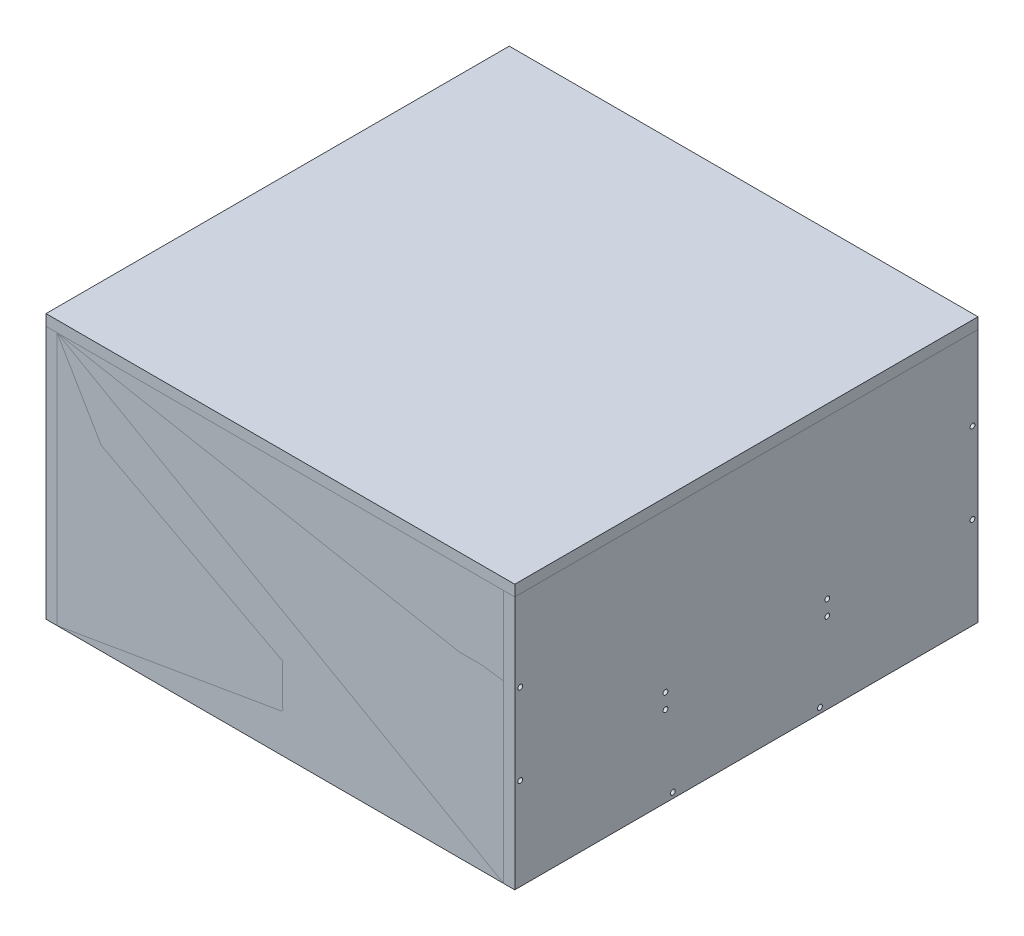
SolidWorks part; units mm, degrees
ref_plane "Front Plane" through (0, 0, 0) normal (0, 0, 1) x (1, 0, 0)
ref_plane "Top Plane" through (0, 0, 0) normal (0, 1, 0) x (1, 0, 0)
ref_plane "Right Plane" through (0, 0, 0) normal (1, 0, 0) x (0, 0, -1)
sketch "Sketch1" plane through (0, 0, 0) normal (0, 1, 0) x (1, 0, 0)
  line L1 (0, 0) -> (257.175, 0)
  line L2 (0, 0) -> (0, 254)
  line L3 (0, 254) -> (257.175, 254)
  line L4 (257.175, 0) -> (257.175, 254)
  dimension "D1" = 257.175
  dimension "D2" = 254
extrude "Boss-Extrude1" add sketch "Sketch1" against normal blind 6.35
sketch "Sketch2" plane through (0, 0, 0) normal (0, 0, 1) x (1, 0, 0)
  line L0 (257.175, -6.35) -> (257.175, 0) construction
  line L1 (0, -6.35) -> (257.175, -6.35)
  line L2 (0, -6.35) -> (0, 139.7)
  line L3 (0, 139.7) -> (257.175, 139.7)
  line L4 (257.175, -6.35) -> (257.175, 139.7)
  dimension "D1" = 146.05
extrude "Boss-Extrude2" add sketch "Sketch2" along normal blind 6.35 separate body
sketch "Sketch3" plane through (0, 0, 0) normal (0, -1, 0) x (1, 0, 0)
  line L0 (0, -127) -> (-23.5534, -127)
  line L1 (0, -254) -> (0, 0) construction
  line L2 (0, -127) -> (0, -138.9854)
ref_plane "Plane2" through (0, 0, -127) normal (0, 0, -1) x (-1, 0, 0)
mirror "Mirror1" about plane through (0, 0, -127) normal (0, 0, -1) of bodies 102
sketch "Sketch4" plane through (0, 0, 0) normal (-1, 0, 0) x (0, 0, 1)
  line L1 (-260.35, -6.35) -> (6.35, -6.35)
  line L2 (-260.35, -6.35) -> (-260.35, 139.7)
  line L3 (-260.35, 139.7) -> (6.35, 139.7)
  line L4 (6.35, -6.35) -> (6.35, 139.7)
extrude "Boss-Extrude3" add sketch "Sketch4" along normal blind 6.35 separate body
sketch "Sketch5" plane through (0, -6.35, 0) normal (0, -1, 0) x (1, 0, 0)
  line L0 (128.5875, 0) -> (-138.2478, 0)
  line L1 (0, 0) -> (257.175, 0) construction
ref_plane "Plane3" through (128.5875, -6.35, 0) normal (-1, 0, 0) x (0, 0, 1)
mirror "Mirror2" about plane through (128.5875, -6.35, 0) normal (-1, 0, 0) of bodies 104
sketch "Sketch6" plane through (0, 0, 0) normal (0, -1, 0) x (1, 0, 0)
  line L0 (128.5875, 0) -> (128.5875, -254)
  line L1 (0, 0) -> (257.175, 0) construction
  line L2 (257.175, -254) -> (0, -254) construction
  line L4 (122.2375, 0) -> (134.9375, 0)
  line L5 (122.2375, 0) -> (122.2375, -254)
  line L6 (122.2375, -254) -> (134.9375, -254)
  line L7 (134.9375, 0) -> (134.9375, -254)
  line L8 (122.2375, 0) -> (134.9375, -254) construction
  line L9 (122.2375, -254) -> (134.9375, 0) construction
  point P6 (128.5875, -127)
  dimension "D1" = 12.7
extrude "Boss-Extrude4" add sketch "Sketch6" against normal blind 57.15 separate body contours L5 L6 L7 L4
sketch "Sketch8" plane through (0, 57.15, 0) normal (0, 1, 0) x (-1, 0, 0)
  line L0 (-128.5875, -254) -> (-128.5875, -173.5667) construction
  line L2 (-122.2375, -254) -> (-134.9375, -254) construction
  line L3 (-128.5875, 0) -> (-128.5875, -80.4333) construction
  line L4 (-122.2375, 0) -> (-134.9375, 0) construction
  line L5 (-122.2375, 0) -> (-122.2375, -254) construction
  line L6 (-134.9375, -86.7833) -> (-122.2375, -86.7833)
  line L7 (-134.9375, -86.7833) -> (-134.9375, -74.0833)
  line L8 (-134.9375, -74.0833) -> (-122.2375, -74.0833)
  line L9 (-122.2375, -86.7833) -> (-122.2375, -74.0833)
  line L10 (-134.9375, -86.7833) -> (-122.2375, -74.0833) construction
  line L11 (-134.9375, -74.0833) -> (-122.2375, -86.7833) construction
  line L13 (-134.9375, -179.9167) -> (-122.2375, -179.9167)
  line L14 (-134.9375, -179.9167) -> (-134.9375, -167.2167)
  line L15 (-134.9375, -167.2167) -> (-122.2375, -167.2167)
  line L16 (-122.2375, -179.9167) -> (-122.2375, -167.2167)
  line L17 (-134.9375, -179.9167) -> (-122.2375, -167.2167) construction
  line L18 (-134.9375, -167.2167) -> (-122.2375, -179.9167) construction
  dimension "D1" = 80.4333
  dimension "D2" = 12.7
extrude "Cut-Extrude1" cut sketch "Sketch8" against normal blind 25.4
sketch "Sketch11" plane through (0, 31.75, 0) normal (0, 1, 0) x (-1, 0, 0)
  line L0 (-134.9375, -173.5667) -> (-128.5875, -173.5667) construction
  line L1 (0, -179.9167) -> (-257.175, -179.9167)
  line L2 (0, -179.9167) -> (0, -167.2167)
  line L3 (0, -167.2167) -> (-257.175, -167.2167)
  line L4 (-257.175, -179.9167) -> (-257.175, -167.2167)
  line L5 (0, -179.9167) -> (-257.175, -167.2167) construction
  line L6 (0, -167.2167) -> (-257.175, -179.9167) construction
  line L7 (-134.9375, -167.2167) -> (-134.9375, -179.9167) construction
  line L9 (0, -254) -> (0, 0) construction
  line L10 (-128.5875, -167.2167) -> (-128.5875, -173.5667) construction
  point P0 (-128.5875, -173.5667)
  dimension "D1" = 12.7
  dimension "D2" = 6.35
extrude "Boss-Extrude6" add sketch "Sketch11" along normal blind 25.4 separate body
mirror "Mirror3" about plane through (0, 0, -127) normal (0, 0, -1) of bodies 113
ref_plane "Plane4" through (257.175, 0, 0) normal (1, 0, 0) x (0, 0, -1)
sketch "Sketch21" plane through (-6.35, 0, 0) normal (-1, 0, 0) x (0, 0, 1)
  line L0 (-80.4333, 31.75) -> (-80.4333, 40.132) construction
  line L2 (-86.7833, 31.75) -> (-74.0833, 31.75) construction
  line L3 (-80.4333, 57.15) -> (-80.4333, 48.768) construction
  line L4 (-74.0833, 57.15) -> (-86.7833, 57.15) construction
  line L5 (-127, 57.15) -> (-127, 14.4604) construction
  line L6 (-86.7833, 57.15) -> (-167.2167, 57.15) construction
  line L7 (-173.5667, 31.75) -> (-173.5667, 40.132) construction
  line L8 (-173.5667, 57.15) -> (-173.5667, 48.768) construction
  line L9 (-257.175, 139.7) -> (-257.175, 93.1333) construction
  line L10 (-260.35, 139.7) -> (-254, 139.7) construction
  line L11 (-257.175, 0) -> (-257.175, 46.5667) construction
  line L12 (-254, -3.175) -> (-257.175, -3.175) construction
  line L13 (-254, -6.35) -> (-254, 0) construction
  line L14 (0, -3.175) -> (3.175, -3.175) construction
  line L15 (3.175, 0) -> (3.175, 46.5667) construction
  line L16 (3.175, 139.7) -> (3.175, 93.1333) construction
  line L17 (-254, -3.175) -> (-169.3418, -3.175) construction
  line L18 (0, -3.175) -> (-84.6582, -3.175) construction
  dimension "D1" = 8.382
  dimension "D2" = 46.5667
  dimension "D3" = 84.6582
hole_wizard "#4-40 Tapped Hole5" positions "3DSketch5" profile "Sketch23" tap size "#4-40" standard "Ansi Inch" end condition through all
sketch3d "3DSketch5"
  line L1 (-6.35, 139.7, 6.35) -> (-6.35, 139.7, -260.35) construction
  line L6 (-6.35, -6.35, -260.35) -> (-6.35, -6.35, 6.35) construction
  point P0 (-6.35, 93.1333, -257.175)
  point P3 (-6.35, 46.5667, -257.175)
  point P9 (-6.35, -3.175, -169.3418)
  point P12 (-6.35, -3.175, -84.6582)
  point P15 (-6.35, 40.132, -173.5667)
  point P18 (-6.35, 48.768, -173.5667)
  point P21 (-6.35, 48.768, -80.4333)
  point P24 (-6.35, 40.132, -80.4333)
  point P27 (-6.35, 46.5667, 3.175)
  point P30 (-6.35, 93.1333, 3.175)
  dimension "D1" = 46.5667
  dimension "D2" = 52.9167
sketch "Sketch23" plane through (-6.35, 93.1333, -257.175) normal (0, 1, 0) x (0, 0, 1)
  line L0 (0, 0) -> (0, 269.875)
  line L1 (0, 269.875) -> (1.397, 269.875)
  line L2 (1.397, 269.875) -> (1.397, 0)
  line L3 (263.525, 269.875) -> (-3.175, 269.875) construction
  line L5 (1.397, 0) -> (0, 0)
  line L11 (0, -6.35) -> (0, 107.95) construction
  dimension "Thread Major Dia." = 2.794
  dimension "Thru Tap Drill Depth" = 269.875
sketch "Sketch24" plane through (0, 0, 0) normal (0, 0, 1) x (1, 0, 0)
  line L0 (128.5875, 57.15) -> (128.5875, 40.2167) construction
  line L1 (122.2375, 57.15) -> (134.9375, 57.15) construction
  line L2 (128.5875, 140.4094) -> (128.5875, -153.1094) construction
  line L3 (128.5875, 0) -> (128.5875, 16.9333) construction
  line L4 (0, 0) -> (257.175, 0) construction
  dimension "D1" = 16.9333
hole_wizard "#4-40 Tapped Hole4" positions "3DSketch6" profile "Sketch25" tap size "#4-40" standard "Ansi Inch" end condition through all
sketch3d "3DSketch6"
  point P0 (128.5875, 40.2167, 0)
  point P3 (128.5875, 16.9333, 0)
sketch "Sketch25" plane through (128.5875, 40.2167, 0) normal (1, 0, 0) x (0, -1, 0)
  line L0 (0, 0) -> (0, 260.35)
  line L1 (0, 260.35) -> (1.397, 260.35)
  line L2 (1.397, 260.35) -> (1.397, 0)
  line L5 (1.397, 0) -> (0, 0)
  line L11 (0, -6.35) -> (0, 107.95) construction
  dimension "Thread Major Dia." = 2.794
  dimension "Thru Tap Drill Depth" = 260.35
sketch "Sketch26" plane through (0, 139.7, 0) normal (0, 1, 0) x (-1, 0, 0)
  line L1 (6.35, 6.35) -> (-263.525, 6.35)
  line L2 (6.35, 6.35) -> (6.35, -260.35)
  line L3 (6.35, -260.35) -> (-263.525, -260.35)
  line L4 (-263.525, 6.35) -> (-263.525, -260.35)
extrude "Boss-Extrude7" add sketch "Sketch26" along normal blind 6.35 separate body
sketch "Sketch34" plane through (263.525, 0, 0) normal (1, 0, 0) x (0, 0, -1)
  line L0 (257.175, 93.1333) -> (260.35, 93.1333)
  line L1 (260.35, 139.7) -> (260.35, -6.35) construction
  line L2 (257.175, 46.5667) -> (260.35, 46.5667)
  line L5 (169.3418, -3.175) -> (169.3418, -6.35)
  line L6 (260.35, -6.35) -> (-6.35, -6.35) construction
  line L7 (127, 139.7) -> (127, -6.35) construction
  line L8 (-6.35, 139.7) -> (260.35, 139.7) construction
  line L9 (84.6582, -3.175) -> (84.6582, -6.35)
  line L11 (-3.175, 46.5667) -> (-6.35, 46.5667)
  line L12 (-3.175, 93.1333) -> (-6.35, 93.1333)
sketch "Sketch35" plane through (0, 0, -260.35) normal (0, 0, -1) x (-1, 0, 0)
  line L0 (-263.525, 93.1333) -> (-224.4298, 93.1333) construction
  line L1 (-263.525, 46.5667) -> (-224.4298, 46.5667) construction
  line L2 (-257.175, 94.5303) -> (-257.175, 91.7363)
  line L3 (-231.775, 89.9583) -> (-231.775, 96.3083)
  line L4 (-257.175, -6.35) -> (-257.175, 139.7) construction
  line L5 (-257.175, -6.35) -> (-257.175, 139.7) construction
  line L6 (-257.175, 47.9637) -> (-257.175, 45.1697)
  line L7 (-231.775, 43.3917) -> (-231.775, 49.7417)
  line L8 (-244.475, 89.9583) -> (-244.475, 91.7363)
  line L9 (-244.475, 96.3083) -> (-231.775, 96.3083)
  line L10 (-244.475, 89.9583) -> (-231.775, 89.9583)
  line L11 (-257.175, 94.5303) -> (-244.475, 94.5303)
  line L12 (-263.525, 139.7) -> (-263.525, -6.35) construction
  line L13 (-257.175, 91.7363) -> (-244.475, 91.7363)
  line L14 (-244.475, 43.3917) -> (-244.475, 45.1697)
  line L15 (-244.475, 94.5303) -> (-244.475, 96.3083)
  line L16 (-263.525, 66.675) -> (-143.2647, 66.675) construction
  line L17 (-244.475, 49.7417) -> (-231.775, 49.7417)
  line L18 (-244.475, 43.3917) -> (-231.775, 43.3917)
  line L19 (-257.175, 47.9637) -> (-244.475, 47.9637)
  line L20 (-257.175, 45.1697) -> (-244.475, 45.1697)
  line L21 (-244.475, 47.9637) -> (-244.475, 49.7417)
  line L22 (6.35, 46.5667) -> (-32.7452, 46.5667) construction
  line L23 (6.35, 93.1333) -> (-32.7452, 93.1333) construction
  line L24 (-128.5875, 139.7) -> (-128.5875, 111.9581) construction
  line L25 (-257.175, 139.7) -> (0, 139.7) construction
  line L26 (-12.7, 47.9637) -> (-12.7, 49.7417)
  line L27 (0, 45.1697) -> (-12.7, 45.1697)
  line L28 (0, 47.9637) -> (-12.7, 47.9637)
  line L29 (-12.7, 43.3917) -> (-25.4, 43.3917)
  line L30 (-12.7, 49.7417) -> (-25.4, 49.7417)
  line L31 (-12.7, 94.5303) -> (-12.7, 96.3083)
  line L32 (-12.7, 43.3917) -> (-12.7, 45.1697)
  line L33 (0, 91.7363) -> (-12.7, 91.7363)
  line L34 (0, 94.5303) -> (-12.7, 94.5303)
  line L35 (-12.7, 89.9583) -> (-25.4, 89.9583)
  line L36 (-12.7, 96.3083) -> (-25.4, 96.3083)
  line L37 (-12.7, 89.9583) -> (-12.7, 91.7363)
  line L38 (-25.4, 43.3917) -> (-25.4, 49.7417)
  line L39 (0, 47.9637) -> (0, 45.1697)
  line L40 (-25.4, 89.9583) -> (-25.4, 96.3083)
  line L41 (0, 94.5303) -> (0, 91.7363)
  line L42 (-257.175, 139.7) -> (-257.175, -6.35) construction
  point P0 (-257.175, 93.1333)
  point P4 (-257.175, 46.5667)
  point P11 (-231.775, 93.1333)
  point P22 (-231.775, 46.5667)
  dimension "D1" = 2.794
  dimension "D2" = 12.7
  dimension "D3" = 6.35
  dimension "D4" = 12.7
  dimension "D5" = 6.35
  dimension "D6" = 12.7
  dimension "D7" = 2.794
  dimension "D8" = 12.7
extrude "Cut-Extrude2" cut sketch "Sketch35" against normal blind 6.35
sketch "Sketch38" plane through (-6.35, 0, 0) normal (-1, 0, 0) x (0, 0, 1)
  line L0 (-127, -6.35) -> (-140.9104, -6.35)
  line L1 (-260.35, -6.35) -> (6.35, -6.35) construction
ref_plane "Plane5" through (-6.35, -6.35, -127) normal (0, 0, -1) x (-1, 0, 0)
mirror "Mirror7" about plane through (-6.35, -6.35, -127) normal (0, 0, -1) of bodies 147
sketch "Sketch39" plane through (0, -6.35, 0) normal (0, -1, 0) x (1, 0, 0)
  line L0 (263.525, -169.3418) -> (-6.35, -169.3418) construction
  line L1 (-6.35, -260.35) -> (-6.35, 6.35) construction
  line L2 (263.525, -84.6582) -> (-6.35, -84.6582) construction
  line L3 (-6.35, -84.6582) -> (25.4, -84.6582) construction
  line L4 (0, -83.2612) -> (0, -86.0552)
  line L5 (25.4, -87.8332) -> (25.4, -81.4832)
  line L6 (12.7, -87.8332) -> (12.7, -86.0552)
  line L7 (12.7, -81.4832) -> (25.4, -81.4832)
  line L8 (12.7, -87.8332) -> (25.4, -87.8332)
  line L9 (0, -83.2612) -> (12.7, -83.2612)
  line L10 (0, -86.0552) -> (12.7, -86.0552)
  line L11 (12.7, -83.2612) -> (12.7, -81.4832)
  line L13 (0, -260.35) -> (0, 6.35) construction
  line L14 (-6.35, -169.3418) -> (19.2534, -169.3418) construction
  line L15 (0, -167.9448) -> (0, -170.7388)
  line L16 (25.4, -172.5168) -> (25.4, -166.1668)
  line L17 (12.7, -172.5168) -> (12.7, -170.7388)
  line L18 (12.7, -166.1668) -> (25.4, -166.1668)
  line L19 (12.7, -172.5168) -> (25.4, -172.5168)
  line L20 (0, -167.9448) -> (12.7, -167.9448)
  line L21 (0, -170.7388) -> (12.7, -170.7388)
  line L22 (12.7, -167.9448) -> (12.7, -166.1668)
  line L23 (0, -254) -> (0, 0) construction
  line L24 (128.5875, 6.35) -> (128.5875, -33.1685) construction
  line L25 (0, 6.35) -> (257.175, 6.35) construction
  line L26 (263.525, -169.3418) -> (237.9216, -169.3418) construction
  line L27 (263.525, -84.6582) -> (231.775, -84.6582) construction
  line L28 (244.475, -167.9448) -> (244.475, -166.1668)
  line L29 (257.175, -170.7388) -> (244.475, -170.7388)
  line L30 (257.175, -167.9448) -> (244.475, -167.9448)
  line L31 (244.475, -172.5168) -> (231.775, -172.5168)
  line L32 (244.475, -166.1668) -> (231.775, -166.1668)
  line L33 (244.475, -172.5168) -> (244.475, -170.7388)
  line L34 (231.775, -172.5168) -> (231.775, -166.1668)
  line L35 (257.175, -167.9448) -> (257.175, -170.7388)
  line L36 (244.475, -83.2612) -> (244.475, -81.4832)
  line L37 (257.175, -86.0552) -> (244.475, -86.0552)
  line L38 (257.175, -83.2612) -> (244.475, -83.2612)
  line L39 (244.475, -87.8332) -> (231.775, -87.8332)
  line L40 (244.475, -81.4832) -> (231.775, -81.4832)
  line L41 (244.475, -87.8332) -> (244.475, -86.0552)
  line L42 (231.775, -87.8332) -> (231.775, -81.4832)
  line L43 (257.175, -83.2612) -> (257.175, -86.0552)
  point P13 (25.4, -84.6582)
  point P20 (0, -169.3418)
  point P25 (25.4, -169.3418)
  dimension "D1" = 6.35
  dimension "D2" = 12.7
  dimension "D3" = 2.794
  dimension "D4" = 12.7
  dimension "D5" = 6.35
  dimension "D6" = 12.7
  dimension "D7" = 2.794
  dimension "D8" = 12.7
extrude "Cut-Extrude3" cut sketch "Sketch39" against normal blind 6.35
sketch "Sketch42" plane through (0, 0, -254) normal (0, 0, -1) x (-1, 0, 0)
  line L0 (-128.5875, 40.2167) -> (-122.2375, 40.2167)
  line L1 (-122.2375, 57.15) -> (-122.2375, 0) construction
  line L2 (-128.5875, 16.9333) -> (-122.2375, 16.9333)
sketch "Sketch43" plane through (122.2375, 0, 0) normal (-1, 0, 0) x (0, 0, 1)
  line L0 (-254, 40.2167) -> (0, 40.2167) construction
  line L1 (0, 57.15) -> (0, 0) construction
  line L2 (-254, 16.9333) -> (0, 16.9333) construction
  line L3 (-254, 16.9333) -> (-221.2548, 16.9333) construction
  line L4 (-254, 18.3303) -> (-254, 15.5363)
  line L5 (-228.6, 13.7583) -> (-228.6, 20.1083)
  line L6 (-241.3, 13.7583) -> (-241.3, 15.5363)
  line L7 (-241.3, 20.1083) -> (-228.6, 20.1083)
  line L8 (-241.3, 13.7583) -> (-228.6, 13.7583)
  line L9 (-254, 18.3303) -> (-241.3, 18.3303)
  line L10 (-254, 15.5363) -> (-241.3, 15.5363)
  line L11 (-241.3, 18.3303) -> (-241.3, 20.1083)
  line L12 (-254, 57.15) -> (-254, 0) construction
  line L13 (-254, 28.575) -> (-219.3101, 28.575) construction
  line L14 (-254, 40.2167) -> (-221.2548, 40.2167) construction
  line L15 (-241.3, 38.8197) -> (-241.3, 37.0417)
  line L16 (-254, 41.6137) -> (-241.3, 41.6137)
  line L17 (-254, 38.8197) -> (-241.3, 38.8197)
  line L18 (-241.3, 43.3917) -> (-228.6, 43.3917)
  line L19 (-241.3, 37.0417) -> (-228.6, 37.0417)
  line L20 (-241.3, 43.3917) -> (-241.3, 41.6137)
  line L21 (-228.6, 43.3917) -> (-228.6, 37.0417)
  line L22 (-254, 38.8197) -> (-254, 41.6137)
  line L23 (-127, 57.15) -> (-127, 45.6306) construction
  line L24 (-86.7833, 57.15) -> (-167.2167, 57.15) construction
  line L25 (-127, 139.7) -> (-127, -6.35) construction
  line L26 (0, 40.2167) -> (-32.7452, 40.2167) construction
  line L27 (0, 28.575) -> (-34.6899, 28.575) construction
  line L28 (0, 16.9333) -> (-32.7452, 16.9333) construction
  line L29 (0, 38.8197) -> (0, 41.6137)
  line L30 (-25.4, 43.3917) -> (-25.4, 37.0417)
  line L31 (-12.7, 43.3917) -> (-12.7, 41.6137)
  line L32 (-12.7, 37.0417) -> (-25.4, 37.0417)
  line L33 (-12.7, 43.3917) -> (-25.4, 43.3917)
  line L34 (0, 38.8197) -> (-12.7, 38.8197)
  line L35 (0, 41.6137) -> (-12.7, 41.6137)
  line L36 (-12.7, 38.8197) -> (-12.7, 37.0417)
  line L37 (-12.7, 18.3303) -> (-12.7, 20.1083)
  line L38 (0, 15.5363) -> (-12.7, 15.5363)
  line L39 (0, 18.3303) -> (-12.7, 18.3303)
  line L40 (-12.7, 13.7583) -> (-25.4, 13.7583)
  line L41 (-12.7, 20.1083) -> (-25.4, 20.1083)
  line L42 (-12.7, 13.7583) -> (-12.7, 15.5363)
  line L43 (-25.4, 13.7583) -> (-25.4, 20.1083)
  line L44 (0, 18.3303) -> (0, 15.5363)
  point P8 (-254, 16.9333)
  point P13 (-228.6, 16.9333)
  dimension "D1" = 6.35
  dimension "D2" = 12.7
  dimension "D3" = 2.794
  dimension "D4" = 12.7
extrude "Cut-Extrude4" cut sketch "Sketch43" against normal blind 12.7
